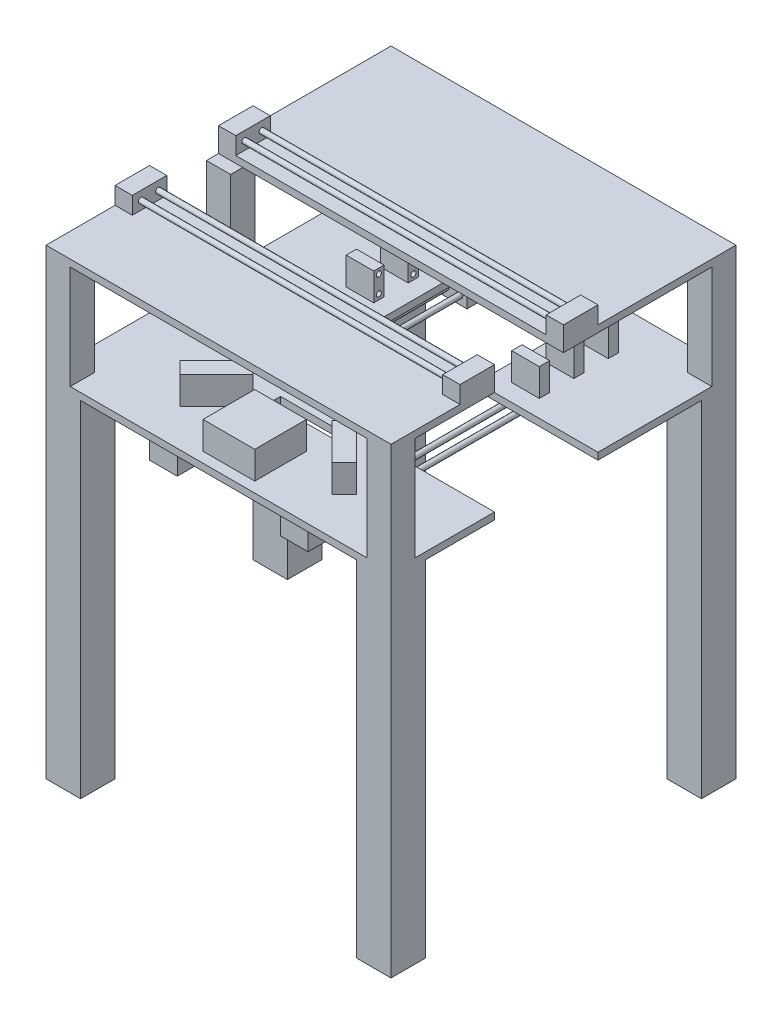
SolidWorks part; units mm, degrees
ref_plane "Front Plane" through (0, 0, 0) normal (0, 0, 1) x (1, 0, 0)
ref_plane "Top Plane" through (0, 0, 0) normal (0, 1, 0) x (1, 0, 0)
ref_plane "Right Plane" through (0, 0, 0) normal (1, 0, 0) x (0, 0, -1)
sketch "Sketch1" plane through (0, 0, 0) normal (0, 1, 0) x (1, 0, 0)
  line L1 (0, 0) -> (-1000, 0)
  line L2 (0, 0) -> (0, 1000)
  line L3 (0, 1000) -> (-1000, 1000)
  line L4 (-1000, 0) -> (-1000, 1000)
  dimension "D1" = 1000
  dimension "D2" = 1000
extrude "Boss-Extrude1" add sketch "Sketch1" along normal blind 20
sketch "Sketch2" plane through (0, 20, 0) normal (0, 1, 0) x (1, 0, 0)
  line L0 (0, 1000) -> (-1000, 1000) construction
  line L1 (-650, 1000) -> (-350, 1000)
  line L2 (-650, 1000) -> (-650, 300)
  line L3 (-650, 300) -> (-350, 300)
  line L4 (-350, 1000) -> (-350, 300)
  line L5 (-1000, 1000) -> (-1000, 0) construction
  point P6 (-500, 1000)
  dimension "D1" = 300
  dimension "D2" = 500
  dimension "D3" = 700
extrude "Cut-Extrude1" cut sketch "Sketch2" against normal blind 20
sketch "Sketch3" plane through (0, 20, 0) normal (0, 1, 0) x (1, 0, 0)
  line L0 (0, 0) -> (0, 1000) construction
  line L1 (-350, 300) -> (0, 300)
  line L2 (-350, 300) -> (-350, 600)
  line L3 (-350, 600) -> (0, 600)
  line L4 (0, 300) -> (0, 600)
  dimension "D1" = 300
extrude "Cut-Extrude2" cut sketch "Sketch3" against normal blind 20
ref_plane "Plane1" through (-500, 0, 0) normal (-1, 0, 0) x (0, 0, 1)
ref_plane "Plane2" through (0, 0, -500) normal (0, 0, 1) x (1, 0, 0)
sketch "Sketch5" plane through (0, 20, 0) normal (0, 1, 0) x (1, 0, 0)
  line L0 (-1000, 1000) -> (-1000, 0) construction
  line L1 (-1000, 930) -> (-930, 930)
  line L2 (-1000, 930) -> (-1000, 1000)
  line L3 (-1000, 1000) -> (-930, 1000)
  line L4 (-930, 930) -> (-930, 1000)
  line L5 (-650, 1000) -> (-1000, 1000) construction
  dimension "D1" = 70
  dimension "D2" = 70
extrude "Boss-Extrude2" add sketch "Sketch5" along normal blind 300
pattern_linear "LPattern1" count 3 spacing 465 along (0, 0, 1) of "Boss-Extrude2"
mirror "Mirror1" about plane through (0, 0, -500) normal (0, 0, 1) of "Boss-Extrude2"
sketch "Sketch6" plane through (0, 20, 0) normal (0, 1, 0) x (1, 0, 0)
  line L0 (0, 1000) -> (-350, 1000) construction
  line L1 (-70, 1000) -> (0, 1000)
  line L2 (-70, 1000) -> (-70, 930)
  line L3 (-70, 930) -> (0, 930)
  line L4 (0, 1000) -> (0, 930)
  line L5 (0, 600) -> (0, 1000) construction
  dimension "D1" = 70
  dimension "D2" = 70
extrude "Boss-Extrude3" add sketch "Sketch6" along normal blind 300
sketch "Sketch7" plane through (0, 320, 0) normal (0, 1, 0) x (1, 0, 0)
  line L0 (-11, 500) -> (11, 500) construction
  line L1 (-1000, 1000) -> (0, 1000)
  line L2 (-1000, 1000) -> (-1000, 500)
  line L3 (-1000, 500) -> (0, 500)
  line L4 (0, 1000) -> (0, 500)
  dimension "D1" = 1000
extrude "Boss-Extrude4" add sketch "Sketch7" along normal blind 20
sketch "Sketch8" plane through (0, 320, 0) normal (0, 1, 0) x (1, 0, 0)
  line L1 (-1000, 0) -> (0, 0)
  line L2 (-1000, 0) -> (-1000, 300)
  line L3 (-1000, 300) -> (0, 300)
  line L4 (0, 0) -> (0, 300)
extrude "Boss-Extrude5" add sketch "Sketch8" along normal blind 20
sketch "Sketch9" plane through (0, 340, 0) normal (0, 1, 0) x (1, 0, 0)
  line L0 (-1000, 1000) -> (-1000, 500) construction
  line L1 (-11, 500) -> (11, 500) construction
  line L2 (-1000, 600) -> (-950, 600)
  line L3 (-1000, 600) -> (-1000, 500)
  line L4 (-1000, 500) -> (-950, 500)
  line L5 (-950, 600) -> (-950, 500)
  dimension "D1" = 50
  dimension "D2" = 100
extrude "Boss-Extrude6" add sketch "Sketch9" along normal blind 50
mirror "Mirror4" about plane through (-500, 0, 0) normal (-1, 0, 0) of "Boss-Extrude6"
sketch "Sketch10" plane through (-950, 0, 0) normal (1, 0, 0) x (0, 0, -1)
  line L0 (500, 390) -> (500, 340) construction
  line L1 (600, 390) -> (600, 340) construction
  line L2 (500, 390) -> (600, 390) construction
  circle A0 centre (525, 365) radius 7.5
  circle A1 centre (575, 365) radius 7.5
  point P8 (575, 365)
  point P11 (0, 0)
  point P12 (0, 0)
  dimension "D1" = 15
  dimension "D2" = 15
  dimension "D3" = 25
  dimension "D4" = 25
  dimension "D5" = 25
  dimension "D6" = 25
extrude "Boss-Extrude7" add sketch "Sketch10" along normal blind 900
sketch "Sketch12" plane through (0, 20, 0) normal (0, 1, 0) x (1, 0, 0)
  line L0 (-650, 250) -> (-614.6447, 214.6447)
  line L1 (-650, 250) -> (-756.066, 143.934)
  line L2 (-614.6447, 214.6447) -> (-720.7107, 108.5786)
  line L3 (-756.066, 143.934) -> (-720.7107, 108.5786)
  line L4 (-650, 1000) -> (-650, 300) construction
  line L7 (0, 300) -> (-1000, 300) construction
  point P0 (-650.1769, 250.0003)
  dimension "D1" = 135
  dimension "D2" = 150
  dimension "D3" = 50
  dimension "D4" = 50
  dimension "D5" = 0
extrude "Boss-Extrude8" add sketch "Sketch12" along normal blind 80
mirror "Mirror5" about plane through (-500, 0, 0) normal (-1, 0, 0) of "Boss-Extrude8"
sketch "Sketch13" plane through (0, 0, 0) normal (0, -1, 0) x (1, 0, 0)
  line L1 (-350.388, -130) -> (-270.388, -130)
  line L2 (-350.388, -130) -> (-350.388, -30)
  line L3 (-350.388, -30) -> (-270.388, -30)
  line L4 (-270.388, -130) -> (-270.388, -30)
  line L6 (-1000, 0) -> (0, 0) construction
  point P5 (-270, -250)
  point P6 (-270.388, -249.7211)
  dimension "D1" = 100
  dimension "D2" = 80
  dimension "D3" = 30
extrude "Boss-Extrude9" add sketch "Sketch13" along normal blind 80
mirror "Mirror6" about plane through (-500, 0, 0) normal (-1, 0, 0) of "Boss-Extrude9"
mirror "Mirror7" about plane through (0, 0, -500) normal (0, 0, 1) of "Mirror6", "Boss-Extrude9"
sketch "Sketch14" plane through (0, 0, -870) normal (0, 0, 1) x (1, 0, 0)
  line L0 (-729.612, -80) -> (-729.612, 0) construction
  line L1 (-649.612, -80) -> (-649.612, 0) construction
  line L2 (-729.612, -80) -> (-649.612, -80) construction
  circle A0 centre (-709.612, -55) radius 7.5
  circle A1 centre (-669.612, -55) radius 7.5
  dimension "D1" = 15
  dimension "D2" = 15
  dimension "D3" = 20
  dimension "D4" = 20
  dimension "D5" = 25
  dimension "D6" = 25
extrude "Boss-Extrude10" add sketch "Sketch14" along normal blind 800
mirror "Mirror8" about plane through (-500, 0, 0) normal (-1, 0, 0) of "Boss-Extrude10"
sketch "Sketch16" plane through (-300, 0, -300) normal (-0.7071, 0, -0.7071) x (-0.7071, 0, 0.7071)
  line L0 (120.7107, 20) -> (70.7107, 20) construction
  line L1 (120.7107, 100) -> (70.7107, 100) construction
  line L2 (120.7107, 100) -> (120.7107, 20) construction
  circle A0 centre (95.7107, 80) radius 7.5
  circle A1 centre (95.7107, 40) radius 7.5
  dimension "D1" = 15
  dimension "D2" = 15
  dimension "D3" = 20
  dimension "D4" = 20
  dimension "D5" = 25
  dimension "D6" = 25
extrude "Cut-Extrude3" cut sketch "Sketch16" against normal blind 140
mirror "Mirror9" about plane through (-500, 0, 0) normal (-1, 0, 0) of "Cut-Extrude3"
sketch "Sketch18" plane through (0, 0, 0) normal (0, -1, 0) x (1, 0, 0)
  line L0 (-350.388, -30) -> (-350.388, -130) construction
  line L1 (-600.388, -280) -> (-400.388, -280)
  line L2 (-600.388, -280) -> (-600.388, -250)
  line L3 (-600.388, -250) -> (-400.388, -250)
  line L4 (-400.388, -280) -> (-400.388, -250)
  line L6 (-650, -300) -> (0, -300) construction
  point P6 (-400, -218.2908)
  dimension "D1" = 30
  dimension "D2" = 200
  dimension "D3" = 50
  dimension "D4" = 20
extrude "Cut-Extrude4" cut sketch "Sketch18" against normal blind 140
sketch "Sketch19" plane through (0, 0, 0) normal (0, -1, 0) x (1, 0, 0)
  line L0 (-400.388, -250) -> (-600.388, -250) construction
  line L1 (-550.388, -250) -> (-450.388, -250)
  line L2 (-550.388, -250) -> (-550.388, -150)
  line L3 (-550.388, -150) -> (-450.388, -150)
  line L4 (-450.388, -250) -> (-450.388, -150)
  line L5 (-350.388, -30) -> (-350.388, -130) construction
  point P6 (-500.388, -150)
  dimension "D1" = 150
  dimension "D2" = 100
  dimension "D3" = 100
extrude "Boss-Extrude11" add sketch "Sketch19" along normal blind 300
sketch "Sketch20" plane through (0, -300, 0) normal (0, -1, 0) x (1, 0, 0)
  line L0 (-550.388, -250) -> (-450.388, -250) construction
  line L1 (-525.388, -250) -> (-475.388, -250)
  line L2 (-525.388, -250) -> (-525.388, -200)
  line L3 (-525.388, -200) -> (-475.388, -200)
  line L4 (-475.388, -250) -> (-475.388, -200)
  line L5 (-550.388, -150) -> (-550.388, -250) construction
  dimension "D1" = 50
  dimension "D2" = 50
  dimension "D3" = 25
extrude "Cut-Extrude5" cut sketch "Sketch20" against normal blind 250 from offset 20 offset against normal yes
sketch "Sketch21" plane through (0, -280, 0) normal (0, 1, 0) x (1, 0, 0)
  line L0 (-475.388, 250) -> (-475.388, 200) construction
  line L1 (-525.388, 250) -> (-475.388, 250) construction
  circle A0 centre (-500.388, 225) radius 7.5
  dimension "D1" = 15
  dimension "D2" = 25
  dimension "D3" = 25
extrude "Boss-Extrude12" add sketch "Sketch21" along normal blind 250
sketch "Sketch22" plane through (0, 20, 0) normal (0, 1, 0) x (1, 0, 0)
  line L0 (-1000, 1000) -> (-1000, 0) construction
  line L2 (-575, 180) -> (-425, 180)
  line L3 (-575, 180) -> (-575, 30)
  line L4 (-575, 30) -> (-425, 30)
  line L5 (-425, 180) -> (-425, 30)
  line L6 (-600.388, 250) -> (-400.388, 250) construction
  point P0 (-414.3661, 30)
  dimension "D1" = 150
  dimension "D2" = 150
  dimension "D3" = 70
  dimension "D4" = 425
extrude "Boss-Extrude13" add sketch "Sketch22" along normal blind 80
sketch "Sketch23" plane through (0, 0, -180) normal (0, 0, -1) x (-1, 0, 0)
  line L0 (425, 20) -> (575, 20) construction
  line L1 (425, 100) -> (425, 20) construction
  line L2 (575, 100) -> (575, 20) construction
  line L3 (425, 100) -> (575, 100) construction
  circle A0 centre (465, 35) radius 7.5
  circle A1 centre (535, 35) radius 7.5
  circle A2 centre (500, 80) radius 7.5
  circle A3 centre (500, 60) radius 7.5
  point P16 (0, 0)
  dimension "D1" = 15
  dimension "D2" = 15
  dimension "D7" = 15
  dimension "D8" = 15
  dimension "D3" = 15
  dimension "D4" = 15
  dimension "D5" = 40
  dimension "D6" = 40
  dimension "D9" = 20
  dimension "D10" = 40
  dimension "D11" = 75
  dimension "D12" = 75
extrude "Cut-Extrude6" cut sketch "Sketch23" against normal blind 140
sketch "Sketch24" plane through (0, 20, 0) normal (0, 1, 0) x (1, 0, 0)
  line L0 (-350, 600) -> (-350, 1000) construction
  line L1 (-300, 680) -> (-220, 680)
  line L2 (-300, 680) -> (-300, 650)
  line L3 (-300, 650) -> (-220, 650)
  line L4 (-220, 680) -> (-220, 650)
  line L5 (0, 600) -> (-350, 600) construction
  dimension "D1" = 50
  dimension "D2" = 80
  dimension "D3" = 30
  dimension "D4" = 50
extrude "Boss-Extrude14" add sketch "Sketch24" along normal blind 80
sketch "Sketch25" plane through (-300, 0, 0) normal (-1, 0, 0) x (0, 0, 1)
  line L0 (-680, 100) -> (-650, 100) construction
  line L1 (-680, 20) -> (-650, 20) construction
  line L2 (-680, 100) -> (-680, 20) construction
  circle A0 centre (-665, 85) radius 7.5
  circle A1 centre (-665, 35) radius 7.5
  point P6 (0, 0)
  dimension "D1" = 15
  dimension "D2" = 15
  dimension "D3" = 15
  dimension "D4" = 15
  dimension "D5" = 15
  dimension "D6" = 15
extrude "Cut-Extrude7" cut sketch "Sketch25" against normal blind 70
pattern_linear "LPattern2" count 3 spacing 100 along (0, 0, -1) of "Boss-Extrude14"
mirror "Mirror11" about plane through (-500, 0, 0) normal (-1, 0, 0) of "LPattern2", "Boss-Extrude14"
pattern_linear "LPattern3" count 3 spacing 100 along (0, 0, -1) of "Cut-Extrude7"
ref_plane "Plane3" through (-649.612, -80, -130) normal (0, 1, 0) x (1, 0, 0)
mirror "Mirror14" about plane through (-500, 0, 0) normal (-1, 0, 0) of "LPattern3", "Cut-Extrude7"
ref_plane "Plane4" through (0, 0, -400) normal (0, 0, 1) x (1, 0, 0)
mirror "Mirror15" about plane through (0, 0, -400) normal (0, 0, 1) of "Boss-Extrude7", "Mirror4", "Boss-Extrude6"
sketch "Sketch32" plane through (0, 0, 0) normal (0, -1, 0) x (1, 0, 0)
  line L0 (-1000, 0) -> (0, 0) construction
  line L1 (-900, 0) -> (-1000, 0)
  line L2 (-900, 0) -> (-900, -100)
  line L3 (-900, -100) -> (-1000, -100)
  line L4 (-1000, 0) -> (-1000, -100)
  line L5 (-1000, -1000) -> (-1000, 0) construction
  dimension "D1" = 100
  dimension "D2" = 100
extrude "Boss-Extrude18" add sketch "Sketch32" along normal blind 1000
mirror "Mirror19" about plane through (0, 0, -500) normal (0, 0, 1) of "Boss-Extrude18" second plane through (-500, 0, 0) second plane normal (-1, 0, 0)
